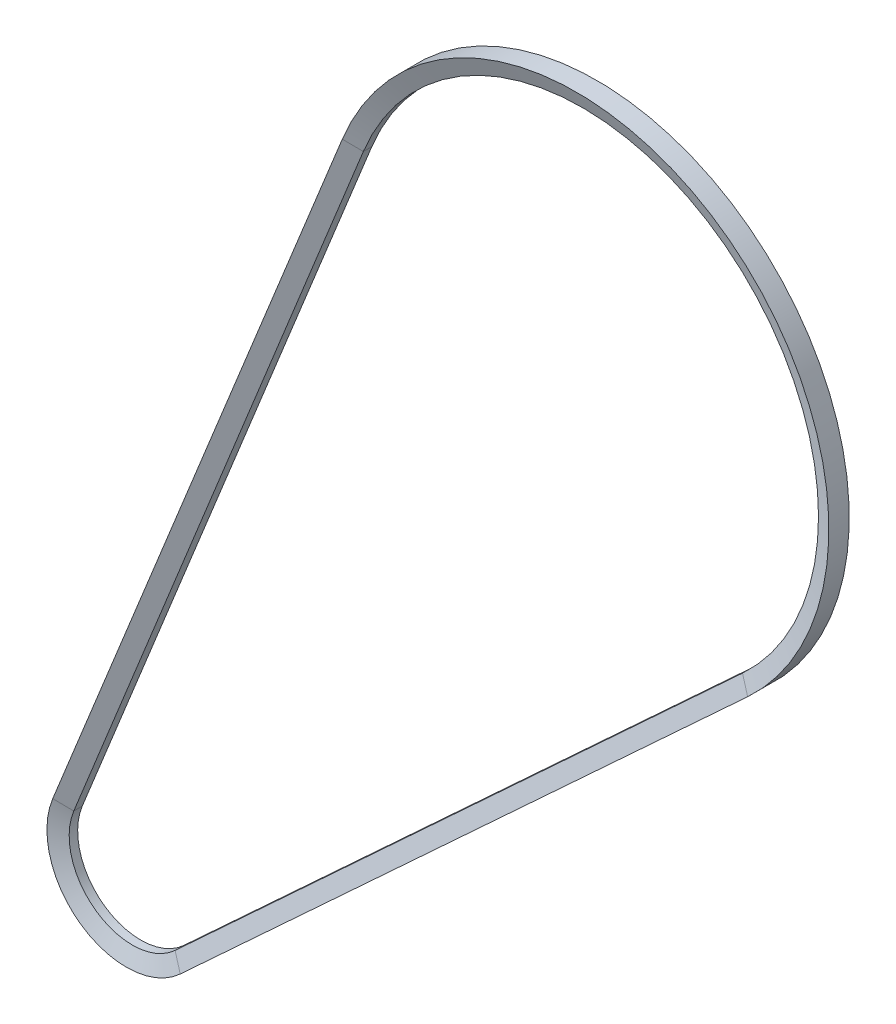
SolidWorks part; units mm, degrees
ref_plane "Front Plane" through (0, 0, 0) normal (0, 0, 1) x (1, 0, 0)
ref_plane "Top Plane" through (0, 0, 0) normal (0, 1, 0) x (1, 0, 0)
ref_plane "Right Plane" through (0, 0, 0) normal (1, 0, 0) x (0, 0, -1)
sketch "Sketch2" plane through (0, 0, 0) normal (0, 0, 1) x (1, 0, 0)
  line L0 (0, 0) -> (1, 0) construction
  line L1 (0, 0) -> (0, 1) construction
  line L2 (-27.8112, 11.2489) -> (114.3904, 362.8208)
  line L3 (299.0059, 235.2011) -> (20.3494, -22.0432)
  arc A0 (20.3494, -22.0432) -> (-27.8112, 11.2489) centre (0, 0) cw
  arc A1 (114.3904, 362.8208) -> (299.0059, 235.2011) centre (221, 319.7) cw
ref_plane "Plane1" through (-27.8112, 11.2489, 0) normal (0.375, 0.927, 0) x (0.927, -0.375, 0)
sketch "Sketch3" plane through (-27.8112, 11.2489, 0) normal (0.375, 0.927, 0) x (0.927, -0.375, 0)
  line L0 (-1, -2.0882) -> (-1, 2.0882)
  line L1 (-1, 2.0882) -> (-9, 5)
  line L2 (-9, 5) -> (-9, -5)
  line L3 (-9, -5) -> (-1, -2.0882)
  line L4 (-1, 0) -> (-7.681, 0) construction
  line L5 (0, 0) -> (-4.2079, 0) construction
  dimension "D1" = 1
  dimension "D2" = 8
  dimension "D3" = 10
  dimension "D4" = 40
sweep "Sweep1" add profiles "Sketch3" path "Sketch2"
